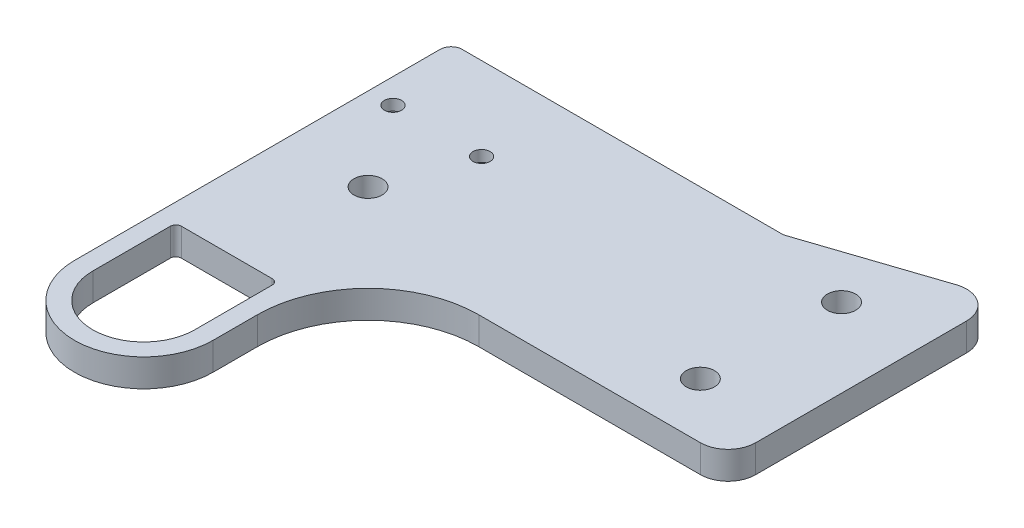
SolidWorks part; units mm, degrees
ref_plane "正面" through (0, 0, 0) normal (0, 0, 1) x (1, 0, 0)
ref_plane "平面" through (0, 0, 0) normal (0, 1, 0) x (1, 0, 0)
ref_plane "右側面" through (0, 0, 0) normal (1, 0, 0) x (0, 0, -1)
sketch "ｽｹｯﾁ1" plane through (0, 0, 0) normal (0, 1, 0) x (1, 0, 0)
  line L0 (0, 0) -> (180, 0) construction
  line L1 (180, 0) -> (180, 60) construction
  line L2 (0, 0) -> (0, -48)
  line L3 (0, -48) -> (25, -48) construction
  line L4 (25, -48) -> (25, -20)
  line L5 (180, 60) -> (0, 0) construction
  line L6 (0, 0) -> (90, 30)
  line L7 (90, 30) -> (90, -20)
  line L8 (90, -20) -> (25, -20)
  line L9 (0, -10) -> (90, -10) construction
  line L10 (90, 19.4591) -> (0, -10.5409) construction
  arc A0 (0, -48) -> (25, -48) centre (12.5, -48) ccw
  circle A1 centre (75.7698, 14.7157) radius 2.55
  circle A2 centre (75, -10) radius 2.55
  circle A3 centre (15, -10) radius 2.55
  circle A4 centre (12.5, -48) radius 7.5
  dimension "D5" = 25
  dimension "D9" = 15
  dimension "D12" = 5.1
  dimension "D13" = 15
  dimension "D1" = 60
  dimension "D2" = 180
  dimension "D3" = 20
  dimension "D4" = 90
  dimension "D6" = 28
  dimension "D7" = 10
  dimension "D8" = 10
  dimension "D10" = 15
  dimension "D11" = 15
extrude "ﾎﾞｽ - 押し出し1" add sketch "ｽｹｯﾁ1" along normal blind 5
fillet "ﾌｨﾚｯﾄ1" radius 20 1 edges at (25, 2.5, 20)
fillet "ﾌｨﾚｯﾄ2" radius 5 2 edges at (90, 2.5, -30) (90, 2.5, 20)
sketch "ｽｹｯﾁ2" plane through (0, 5, 0) normal (0, 1, 0) x (1, 0, 0)
  line L0 (3.3, -48) -> (3.3, -34)
  line L1 (4.3, -33) -> (20.7, -33)
  line L2 (21.7, -34) -> (21.7, -48)
  arc A0 (3.3, -48) -> (21.7, -48) centre (12.5, -48) ccw
  arc A1 (3.3, -34) -> (4.3, -33) centre (4.3, -34) cw
  arc A2 (20.7, -33) -> (21.7, -34) centre (20.7, -34) cw
  point P10 (21.7, -33)
  dimension "D1" = 9.2
  dimension "D3" = 1
  dimension "D2" = 15
extrude "ｶｯﾄ - 押し出し1" cut sketch "ｽｹｯﾁ2" against normal through all
sketch "ｽｹｯﾁ4" plane through (0, 5, 0) normal (0, 1, 0) x (1, 0, 0)
  line L0 (0, 0) -> (0, 20)
  line L1 (0, 20) -> (60, 20)
  line L2 (83.4189, 27.8063) -> (0, 0) construction
  line L3 (60, 20) -> (0, 0)
  dimension "D1" = 20
extrude "ﾎﾞｽ - 押し出し2" add sketch "ｽｹｯﾁ4" against normal up to surface (5 mm away) up to face at (12.5, 0, 39.7976)
sketch "ｽｹｯﾁ3" plane through (0, 5, 0) normal (0, 1, 0) x (1, 0, 0)
  line L0 (12.5, -60.5) -> (12.5, 5) construction
  line L1 (12.5, 5) -> (20.5, 5) construction
  line L2 (20.7, -33) -> (4.3, -33) construction
  arc A0 (0, -48) -> (25, -48) centre (12.5, -48) ccw construction
  circle A1 centre (20.5, 5) radius 1.55
  circle A2 centre (4.5, 5) radius 1.55
  dimension "D1" = 3.1
  dimension "D2" = 38
  dimension "D3" = 8
extrude "ｶｯﾄ - 押し出し2" cut sketch "ｽｹｯﾁ3" against normal through all
fillet "ﾌｨﾚｯﾄ3" radius 2 2 edges at (60, 2.5, -20) (0, 2.5, -20)
sketch "ｽｹｯﾁ5" plane through (0, 0, 0) normal (0, -1, 0) x (1, 0, 0)
  circle A0 centre (4.5, -5) radius 3
  circle A1 centre (20.5, -5) radius 3
  dimension "D1" = 6
extrude "ｶｯﾄ - 押し出し3" cut sketch "ｽｹｯﾁ5" against normal blind 3
